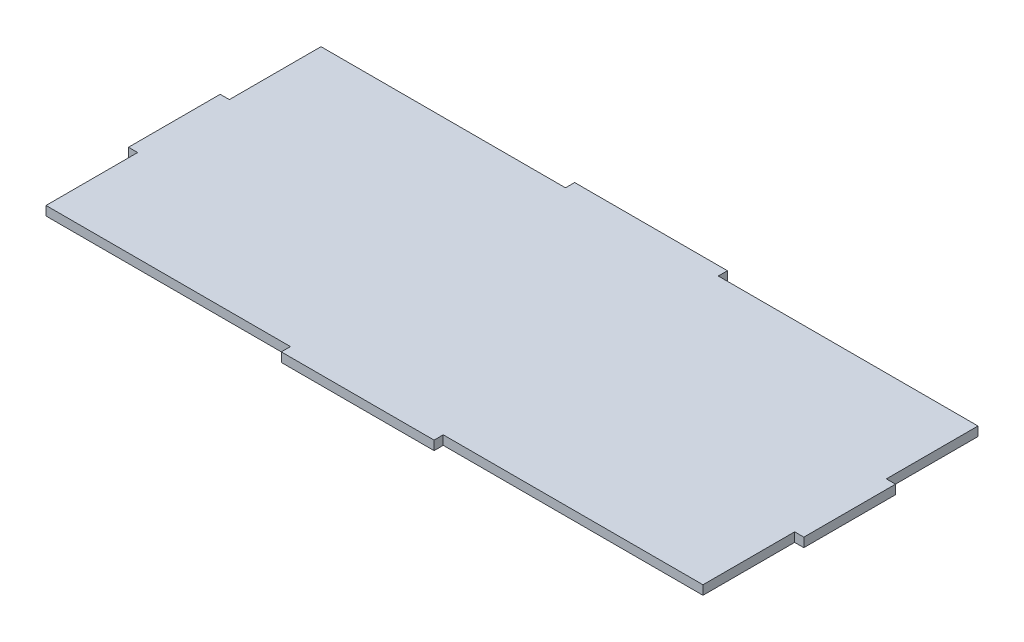
SolidWorks part; units mm, degrees
ref_plane "Front Plane" through (0, 0, 0) normal (0, 0, 1) x (1, 0, 0)
ref_plane "Top Plane" through (0, 0, 0) normal (0, 1, 0) x (1, 0, 0)
ref_plane "Right Plane" through (0, 0, 0) normal (1, 0, 0) x (0, 0, -1)
sketch "Sketch1" plane through (0, 0, 0) normal (0, 1, 0) x (1, 0, 0)
  line L0 (130, 90) -> (215, 90)
  line L1 (0, 0) -> (80, 0)
  line L2 (0, 0) -> (0, 30)
  line L3 (0, 90) -> (80, 90)
  line L4 (215, 0) -> (215, 30)
  line L6 (80, 90) -> (80, 93)
  line L7 (80, 93) -> (130, 93)
  line L8 (130, 90) -> (130, 93)
  line L10 (80, 0) -> (80, -3)
  line L11 (80, -3) -> (130, -3)
  line L12 (130, 0) -> (130, -3)
  line L13 (130, 0) -> (215, 0)
  line L14 (0, 60) -> (0, 90)
  line L15 (215, 60) -> (218, 60)
  line L17 (215, 30) -> (218, 30)
  line L18 (218, 60) -> (218, 30)
  line L19 (0, 60) -> (-3, 60)
  line L21 (0, 30) -> (-3, 30)
  line L22 (-3, 60) -> (-3, 30)
  line L23 (215, 60) -> (215, 90)
  dimension "D1" = 90
  dimension "D2" = 215
  dimension "D3" = 50
  dimension "D4" = 80
  dimension "D5" = 80
  dimension "D6" = 50
  dimension "D7" = 3
  dimension "D8" = 3
  dimension "D9" = 3
  dimension "D10" = 3
  dimension "D11" = 30
  dimension "D12" = 30
  dimension "D13" = 30
  dimension "D14" = 30
extrude "Boss-Extrude1" add sketch "Sketch1" along normal blind 3
